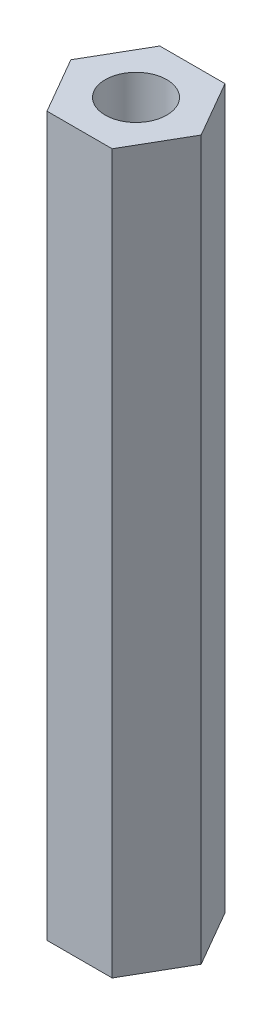
SolidWorks part; units mm, degrees
material "铜"
ref_plane "前视基准面" through (0, 0, 0) normal (0, 0, 1) x (1, 0, 0)
ref_plane "上视基准面" through (0, 0, 0) normal (0, 1, 0) x (1, 0, 0)
ref_plane "右视基准面" through (0, 0, 0) normal (1, 0, 0) x (0, 0, -1)
sketch "草图1" plane through (0, 0, 0) normal (0, 1, 0) x (1, 0, 0)
  line L0 (0, 0) -> (3.1754, 0) construction
  line L1 (3.1754, 0) -> (1.5877, 2.75)
  line L2 (1.5877, 2.75) -> (-1.5877, 2.75)
  line L3 (-1.5877, 2.75) -> (-3.1754, 0)
  line L4 (-3.1754, 0) -> (-1.5877, -2.75)
  line L5 (-1.5877, -2.75) -> (1.5877, -2.75)
  line L6 (1.5877, -2.75) -> (3.1754, 0)
  circle A0 centre (0, 0) radius 2.75 construction
  circle A1 centre (0, 0) radius 1.5
  dimension "D1" = 3
  dimension "D2" = 5.5
extrude "凸台-拉伸1" add sketch "草图1" along normal blind 35
